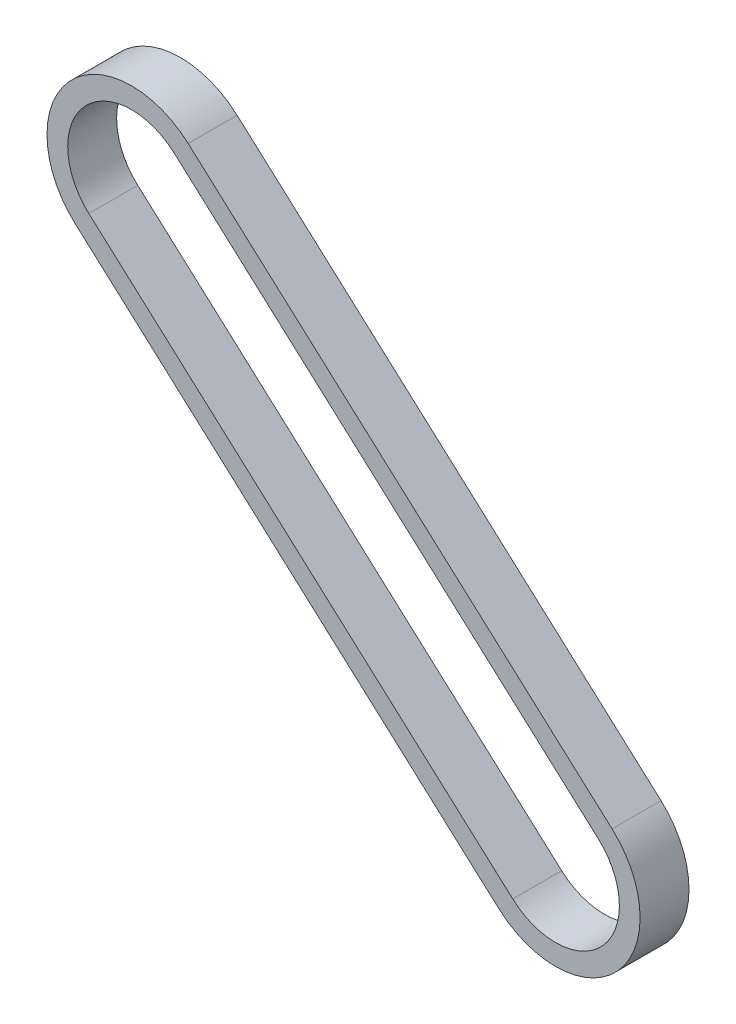
SolidWorks part; units mm, degrees
ref_plane "Front Plane" through (0, 0, 0) normal (0, 0, 1) x (1, 0, 0)
ref_plane "Top Plane" through (0, 0, 0) normal (0, 1, 0) x (1, 0, 0)
ref_plane "Right Plane" through (0, 0, 0) normal (1, 0, 0) x (0, 0, -1)
sketch "Sketch2" plane through (0, 0, 0) normal (0, 0, 1) x (1, 0, 0)
  line L0 (0, 0) -> (1, 0) construction
  line L1 (0, 0) -> (0, 1) construction
  line L2 (-9.2548, -10.2812) -> (-87.2471, 59.9246)
  line L3 (-68.7376, 80.4871) -> (9.2548, 10.2812)
  arc A0 (9.2548, 10.2812) -> (-9.2548, -10.2812) centre (0, 0) cw
  arc A1 (-87.2471, 59.9246) -> (-68.7376, 80.4871) centre (-77.9924, 70.2058) cw
extrude "Extrude-Thin1" add sketch "Sketch2" along normal mid plane 9 thin thin type two direction wall 1.73 second wall 2.08
equation "\"D1@Extrude-Thin1\"=9mm"
